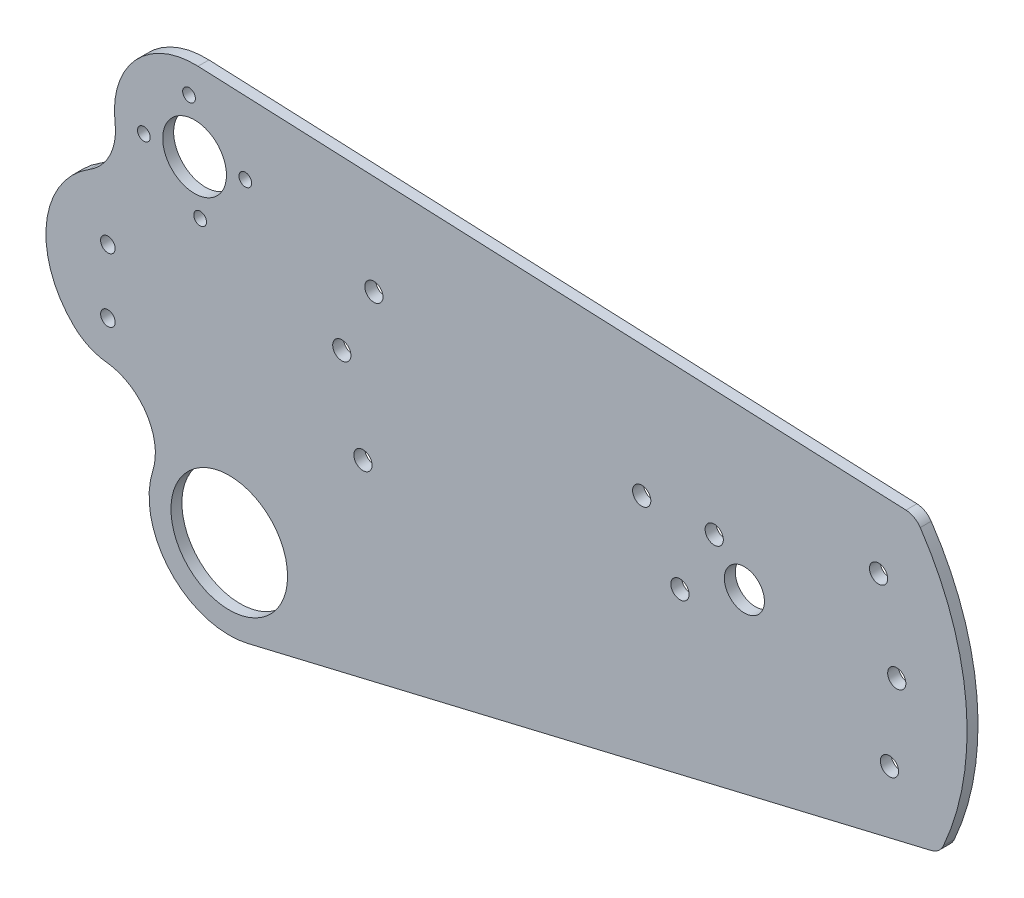
SolidWorks part; units mm, degrees
ref_plane "Front Plane" through (0, 0, 0) normal (0, 0, 1) x (1, 0, 0)
ref_plane "Top Plane" through (0, 0, 0) normal (0, 1, 0) x (1, 0, 0)
ref_plane "Right Plane" through (0, 0, 0) normal (1, 0, 0) x (0, 0, -1)
sketch "Sketch1" plane through (0, 0, 0) normal (0, 0, 1) x (1, 0, 0)
  line L0 (83.305, -33.5) -> (-137.2004, -33.5) construction
  line L1 (-113.5603, 49.4797) -> (80.7216, 41.1353)
  line L2 (-116.9253, 49.6243) -> (-102.5652, -81.605) construction
  line L3 (-99.3111, -80.7362) -> (92.6556, -29.4815) construction
  line L4 (75.1114, 41.3762) -> (83.1431, -32.0213) construction
  line L5 (-109.7453, -15.9904) -> (79.1273, 4.6775) construction
  line L6 (91, -33.5) -> (-88.5, -33.5) construction
  line L7 (-97.4673, 5.5) -> (-155.3054, 5.5) construction
  line L8 (-138.3, -14) -> (-155.3054, -14) construction
  line L9 (-138.3, 5.5) -> (-138.3, -33.5) construction
  line L10 (-155.3054, 5.5) -> (-155.3054, -33.5) construction
  line L11 (36.3824, 33.5) -> (36.3824, -33.5) construction
  line L12 (-111.8477, -83.7242) -> (87.5903, -36.3264)
  line L13 (-91.5, 33.5) -> (88, 33.5) construction
  line L14 (-68.3, -21.5) -> (-108.6591, -25.9164) construction
  circle A0 centre (36.3824, 0) radius 5.5
  circle A1 centre (-114.5043, 27.5) radius 14 construction
  circle A2 centre (-104.9862, -59.4808) radius 14 construction
  arc A3 (-91.5, 33.5) -> (-88.5, -33.5) centre (-18.0922, 3.2198) ccw construction
  circle A4 centre (-68.3, -21.5) radius 2.5
  circle A5 centre (-68.3, -21.5) radius 2.5 construction
  circle A6 centre (-138.3, -5.25) radius 2
  circle A7 centre (-138.3, -22.75) radius 2
  arc A8 (-143.371, 10.0569) -> (-147.5429, -29.3643) centre (-130.3054, -11.2571) ccw
  arc A9 (-147.5429, -29.3643) -> (-137.2004, -33.5) centre (-137.2004, -18.5) ccw
  circle A10 centre (-114.5043, 27.5) radius 22
  arc A11 (87.5903, -36.3264) -> (91, -33.5) centre (86.4343, -31.4619) ccw
  circle A12 centre (-104.9862, -59.4808) radius 22
  arc A13 (91, -33.5) -> (84.6484, 38.9414) centre (22.6589, -2.9929) ccw
  arc A14 (91, -33.5) -> (88, 33.5) centre (22.6589, -2.9929) ccw construction
  arc A15 (84.6484, 38.9414) -> (80.7216, 41.1353) centre (80.507, 36.1399) ccw
  arc A17 (-125.9657, -52.858) -> (-138.7351, -33.4213) centre (-140.2699, -48.3426) ccw
  arc A18 (-143.371, 10.0569) -> (-136.3295, 24.7324) centre (-151.2104, 22.8454) ccw
  circle A19 centre (-74.1, 1.7) radius 2.5
  circle A20 centre (-65.3, 20) radius 2.5
  circle A21 centre (8.2, 8.3) radius 2.5
  circle A22 centre (28.1, 9) radius 2.5
  circle A23 centre (18.7, -8.7) radius 2.5
  circle A25 centre (78.2, -0.1) radius 2.5
  circle A26 centre (76.2, -22) radius 2.5
  circle A27 centre (73.2, 22.3) radius 2.5
  circle A28 centre (73.2, 22.3) radius 2.5 construction
  circle A29 centre (78.2, -0.1) radius 2.5 construction
  circle A30 centre (28.1, 9) radius 2.5 construction
  circle A31 centre (8.2, 8.3) radius 2.5 construction
  circle A32 centre (18.7, -8.7) radius 2.5 construction
  circle A33 centre (76.2, -22) radius 2.5 construction
  circle A34 centre (-74.1, 1.7) radius 2.5 construction
  circle A35 centre (-65.3, 20) radius 2.5 construction
  circle A36 centre (-116.0272, 41.4169) radius 1.75
  circle A37 centre (-100.5874, 29.0229) radius 1.75
  circle A38 centre (-112.9814, 13.5831) radius 1.75
  circle A39 centre (-128.4212, 25.9771) radius 1.75
  circle A40 centre (-106.5091, -45.5639) radius 1.75
  circle A41 centre (-91.0693, -57.9579) radius 1.75
  circle A42 centre (-103.4633, -73.3977) radius 1.75
  circle A43 centre (-118.9031, -61.0037) radius 1.75
  circle A44 centre (36.3824, 0) radius 35 construction
  circle A45 centre (36.3824, 0) radius 43
  circle A49 centre (-104.9862, -59.4808) radius 16
  circle A50 centre (-114.5043, 27.5) radius 16 construction
  circle A51 centre (-114.5043, 27.5) radius 8.75
  circle A52 centre (-104.9862, -59.4808) radius 8.75
  arc A53 (91, -33.5) -> (88, 33.5) centre (22.6589, -2.9929) ccw construction
  point P44 (86.735, -30.7784)
  point P46 (91, -33.5)
  point P52 (79.1273, 4.6775)
  point P109 (-114.5043, 27.5)
  point P118 (-104.9862, -59.4808)
  point P119 (92.6999, -29.3643)
  point P128 (0, 0)
  dimension "D5" = 4
  dimension "D6" = 25
  dimension "D9" = 15
  dimension "D13" = 10
  dimension "D14" = 28
  dimension "D11" = 44
  dimension "D15" = 3.5
  dimension "D12" = 70
  dimension "D19" = 11
  dimension "D20" = 17.5
  dimension "D22" = 32
  dimension "D2" = 39
  dimension "D3" = 70
  dimension "D4" = 17.5
  dimension "D7" = 14
  dimension "D8" = 10
  dimension "D10" = 87.5
  dimension "D21" = 190
  dimension "D23" = 40.6
  dimension "D18" = 8
  dimension "D16" = 4
  dimension "D17" = 4
extrude "Boss-Extrude1" add sketch "Sketch1" along normal blind 3
